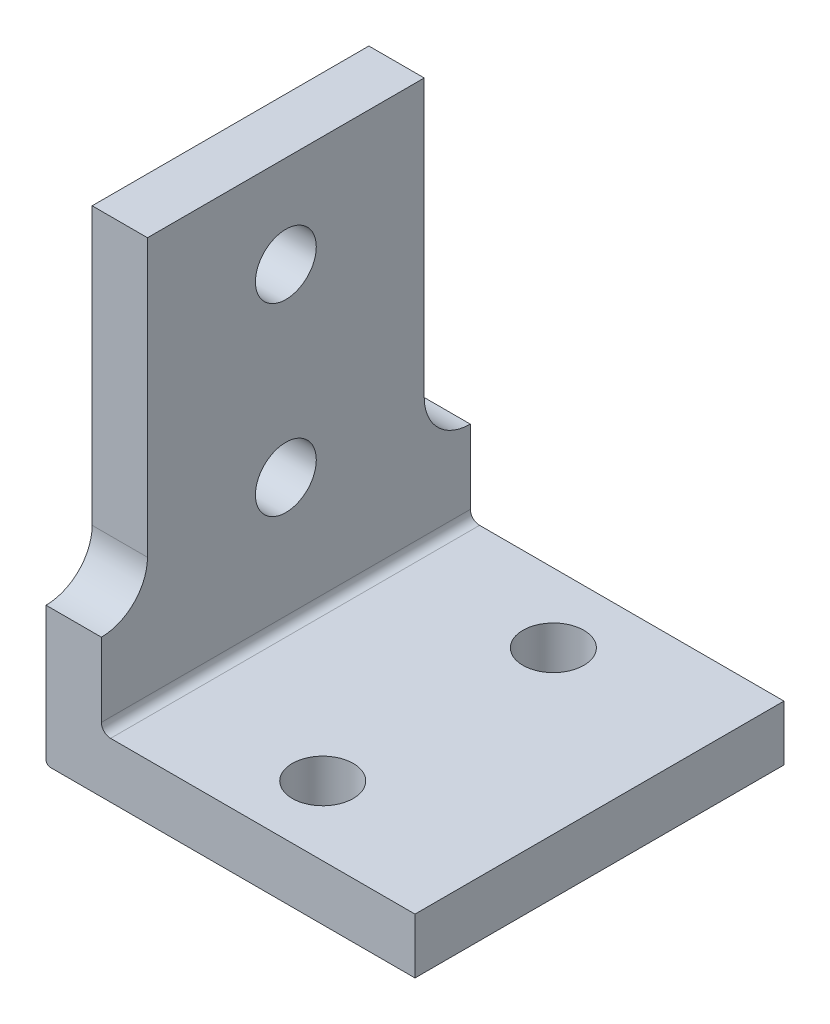
SolidWorks part; units mm, degrees
material "6061-T6 (SS)"
ref_plane "Front Plane" through (0, 0, 0) normal (0, 0, 1) x (1, 0, 0)
ref_plane "Top Plane" through (0, 0, 0) normal (0, 1, 0) x (1, 0, 0)
ref_plane "Right Plane" through (0, 0, 0) normal (1, 0, 0) x (0, 0, -1)
sketch "Sketch1" plane through (0, 0, 0) normal (0, 0, 1) x (1, 0, 0)
  line L0 (0, 0) -> (40, 0)
  line L1 (40, 0) -> (40, 6)
  line L2 (40, 6) -> (6, 6)
  line L3 (6, 6) -> (6, 50)
  line L4 (6, 50) -> (0, 50)
  line L5 (0, 50) -> (0, 0)
  dimension "D1" = 50
  dimension "D2" = 6
  dimension "D3" = 40
extrude "Boss-Extrude1" add sketch "Sketch1" along normal blind 40
sketch "Sketch2" plane through (6, 0, 0) normal (1, 0, 0) x (0, 0, -1)
  line L0 (-20, 40) -> (-20, 20) construction
  line L1 (-40, 50) -> (0, 50) construction
  line L2 (-40, 0) -> (0, 0) construction
  line L3 (-40, 0) -> (0, 0) construction
  point P2 (-20, 0)
  dimension "D1" = 20
  dimension "D2" = 10
hole_wizard "M6 Clearance Hole1" positions "Sketch3" profile "Sketch4" hole size "M6" standard "ISO" end condition through all
sketch "Sketch3" plane through (6, 0, 0) normal (1, 0, 0) x (0, 0, -1)
  point P0 (-20, 40)
  point P3 (-20, 20)
sketch "Sketch4" plane through (6, 40, 20) normal (0, 1, 0) x (0, 0, -1)
  line L0 (0, 0) -> (0, 6)
  line L1 (0, 6) -> (3.3, 6)
  line L2 (3.3, 6) -> (3.3, 0)
  line L5 (3.3, 0) -> (0, 0)
  line L11 (0, -6.35) -> (0, 107.95) construction
  dimension "Thru Hole Dia." = 6.6
  dimension "Thru Hole Depth" = 6
hole_wizard "M6 Clearance Hole2" positions "Sketch5" profile "Sketch6" hole size "M6" standard "ISO" end condition through all
sketch "Sketch5" plane through (0, 0, 0) normal (0, -1, 0) x (-1, 0, 0)
  line L0 (-40, -20) -> (0, -20) construction
  line L1 (-40, -40) -> (-40, 0) construction
  line L2 (0, -40) -> (0, 0) construction
  line L3 (-22.5, -7.5) -> (-22.5, -32.5) construction
  point P9 (-22.5, -7.5)
  point P10 (-22.5, -32.5)
  point P15 (-22.5, -20)
  dimension "D1" = 22.5
  dimension "D2" = 25
sketch "Sketch6" plane through (22.5, 0, 32.5) normal (1, 0, 0) x (0, 0, -1)
  line L0 (0, 0) -> (0, 50)
  line L1 (0, 50) -> (3.3, 50)
  line L2 (3.3, 50) -> (3.3, 0)
  line L5 (3.3, 0) -> (0, 0)
  line L11 (0, -6.35) -> (0, 107.95) construction
  dimension "Thru Hole Dia." = 6.6
  dimension "Thru Hole Depth" = 50
fillet "Fillet1" radius 1 1 edges at (6, 6, 20)
fillet "Fillet2" radius 0.5 1 edges at (0, 0, 20)
sketch "Sketch7" plane through (6, 0, 0) normal (1, 0, 0) x (0, 0, -1)
  line L4 (-5, 50) -> (0, 50)
  line L5 (0, 50) -> (0, 15)
  line L6 (-5, 20) -> (-5, 50)
  line L7 (-20, 50) -> (-20, 0) construction
  line L13 (-40, 50) -> (-40, 7)
  line L14 (-40, 7) -> (0, 7)
  line L15 (0, 7) -> (0, 50)
  line L16 (0, 50) -> (-40, 50)
  line L17 (-40, 50) -> (-40, 7) construction
  line L18 (-40, 7) -> (0, 7) construction
  line L19 (0, 7) -> (0, 50) construction
  line L20 (0, 50) -> (-40, 50) construction
  line L21 (-40, 0) -> (0, 0) construction
  line L22 (-40, 7) -> (-40, 50) construction
  line L23 (-35, 20) -> (-35, 50)
  line L24 (-40, 50) -> (-40, 15)
  line L25 (-35, 50) -> (-40, 50)
  arc A1 (0, 15) -> (-5, 20) centre (0, 20) cw
  arc A2 (-40, 15) -> (-35, 20) centre (-40, 20) ccw
  dimension "D2" = 5
  dimension "D3" = 35
  dimension "D1" = 0
extrude "Cut-Extrude1" cut sketch "Sketch7" against normal through all
